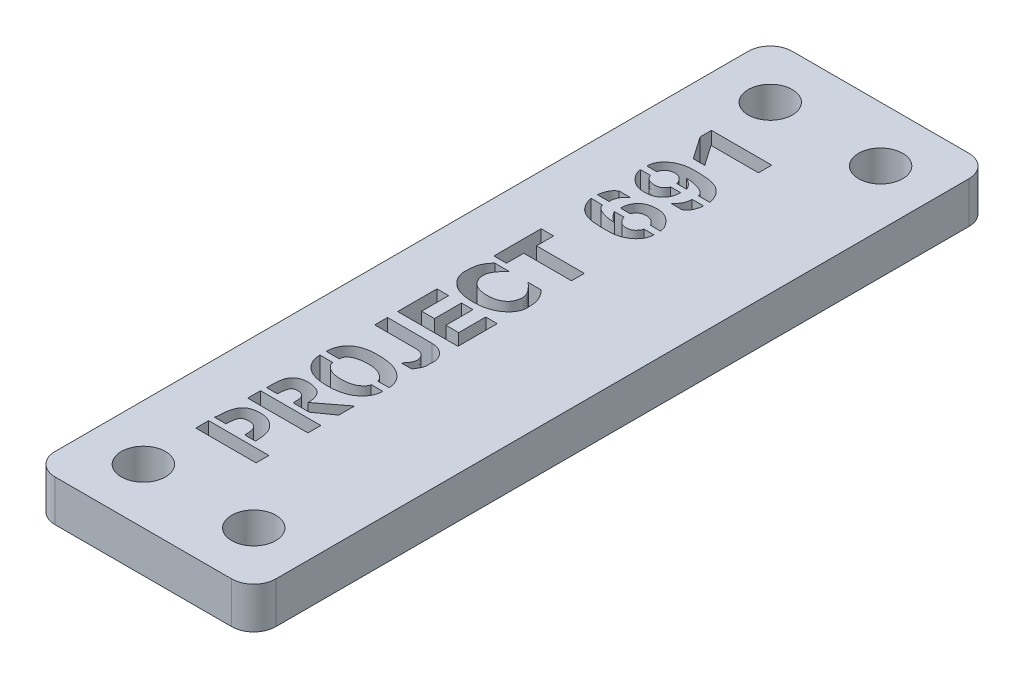
SolidWorks part; units mm, degrees
ref_plane "Front Plane" through (0, 0, 0) normal (0, 0, 1) x (1, 0, 0)
ref_plane "Top Plane" through (0, 0, 0) normal (0, 1, 0) x (1, 0, 0)
ref_plane "Right Plane" through (0, 0, 0) normal (1, 0, 0) x (0, 0, -1)
sketch "Sketch1" plane through (0, 0, 0) normal (0, 1, 0) x (1, 0, 0)
  line L1 (12.7, -42.418) -> (-12.7, -42.418)
  line L2 (12.7, -42.418) -> (12.7, 42.418)
  line L3 (12.7, 42.418) -> (-12.7, 42.418)
  line L4 (-12.7, -42.418) -> (-12.7, 42.418)
  line L5 (12.7, -42.418) -> (-12.7, 42.418) construction
  line L6 (12.7, 42.418) -> (-12.7, -42.418) construction
  point P0 (0, 0)
  dimension "D1" = 84.836
  dimension "D2" = 25.4
extrude "Boss-Extrude1" add sketch "Sketch1" along normal blind 4.7625
fillet "Fillet1" radius 2.54 4 edges at (12.7, 2.3813, 42.418) (-12.7, 2.3813, 42.418) (12.7, 2.3813, -42.418) (-12.7, 2.3813, -42.418)
sketch "Sketch2" plane through (0, 4.7625, 0) normal (0, 1, 0) x (1, 0, 0)
  line L2 (12.7, -39.878) -> (12.7, 39.878) construction
  line L3 (-10.16, -42.418) -> (10.16, -42.418) construction
  line L4 (0, 0) -> (12.7, 0) construction
  line L5 (0, 0) -> (0, -42.418) construction
  circle A0 centre (6.35, 36.068) radius 2.54
  circle A1 centre (-6.35, 36.068) radius 2.54
  circle A2 centre (6.35, -36.068) radius 2.54
  circle A3 centre (-6.35, -36.068) radius 2.54
  dimension "D5" = 5.08
  dimension "D6" = 6.35
  dimension "D7" = 6.35
extrude "Cut-Extrude1" cut sketch "Sketch2" against normal blind 4.7625
sketch "Sketch3" plane through (0, 4.7625, 0) normal (0, 1, 0) x (1, 0, 0)
  line L0 (0, -30.0124) -> (0, 32.7705) construction
  text T0 "PROJECT 691" font "TC_LaserSans" height in points 28
extrude "Cut-Extrude3" cut sketch "Sketch3" against normal blind 4.7625
